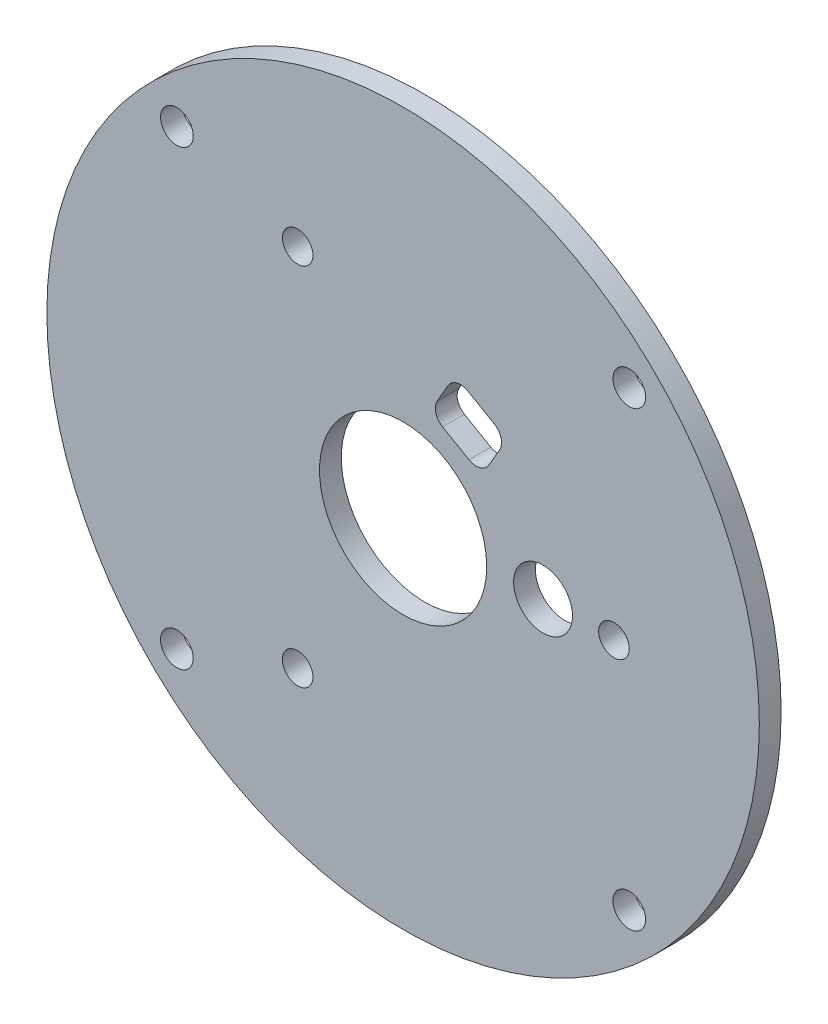
SolidWorks part; units mm, degrees
ref_plane "前视基准面" through (0, 0, 0) normal (0, 0, 1) x (1, 0, 0)
ref_plane "上视基准面" through (0, 0, 0) normal (0, 1, 0) x (1, 0, 0)
ref_plane "右视基准面" through (0, 0, 0) normal (1, 0, 0) x (0, 0, -1)
sketch "草图1" plane through (0, 0, 0) normal (0, 0, 1) x (1, 0, 0)
  line L10 (0, 0) -> (29, 0)
  line L11 (0, 0) -> (-14.5, 25.1147)
  line L12 (0, 0) -> (-14.5, -25.1147)
  circle A2 centre (0, 44) radius 1.6
  circle A4 centre (0, 0) radius 49
  circle A5 centre (44, 0) radius 1.6
  circle A7 centre (0, -44) radius 1.6
  circle A9 centre (-44, 0) radius 1.6
  circle A10 centre (29, 0) radius 2.1
  circle A11 centre (-14.5, 25.1147) radius 2.1
  circle A12 centre (-14.5, -25.1147) radius 2.1
  point P34 (0, 0)
  dimension "D1" = 4
sketch "草图2" plane through (0, 0, 0) normal (0, 0, 1) x (1, 0, 0)
  circle A0 centre (0, 0) radius 11.5
sketch "草图3" plane through (0, 0, 0) normal (0, 0, 1) x (1, 0, 0)
  circle A0 centre (0, 0) radius 8.6
sketch "草图5" plane through (0, 0, 0) normal (1, 0, 0) x (0, 0, -1)
  circle A0 centre (-59.5, 0) radius 1.5
sketch "草图6" plane through (0, 0, 0) normal (0, 0, 1) x (1, 0, 0)
  circle A0 centre (19.25, 0) radius 4.05
sketch "草图7" plane through (0, 0, 0) normal (0, 0, 1) x (1, 0, 0)
  line L3 (10.8022, 10.5058) -> (14.2725, 16.5146)
  line L8 (3.7014, 14.6068) -> (10.8022, 10.5058)
  line L9 (3.7014, 14.6068) -> (7.1717, 20.6156)
  line L10 (7.1717, 20.6156) -> (14.2725, 16.5146)
  dimension "D1" = 14.5
extrude "凸台-拉伸4" add sketch "草图1" along normal blind 13 contours A2 | A7 | A5 | A9 | A12 | A10 | A11
sketch "草图8" plane through (0, 0, 0) normal (0, 0, 1) x (1, 0, 0)
  circle A0 centre (0, 0) radius 49
extrude "凸台-拉伸5" add sketch "草图8" along normal blind 3
sketch "草图9" plane through (0, 0, 0) normal (0, 0, 1) x (1, 0, 0)
  circle A0 centre (0, 44) radius 2.1
  circle A1 centre (44, 0) radius 2.1
  circle A2 centre (0, -44) radius 2.1
  circle A3 centre (-44, 0) radius 2.1
  circle A4 centre (-14.5, 25.1147) radius 2.1
  circle A5 centre (-14.5, -25.1147) radius 2.1
  circle A6 centre (29, 0) radius 2.1
  point P12 (0, 0)
  dimension "D2" = 4.2
  dimension "D1" = 4
extrude "切除-拉伸2" cut sketch "草图9" along normal blind 13
extrude "切除-拉伸3" cut sketch "草图3" along normal blind 13 contours A0
extrude "切除-拉伸4" cut sketch "草图6" along normal blind 13 contours A0
extrude "切除-拉伸5" cut sketch "草图7" along normal blind 13 contours L10 L3 L8 L9
extrude "切除-拉伸6" cut sketch "草图2" along normal blind 13 contours A0
fillet "圆角1" radius 2 4 edges at (7.1717, 20.6156, 1.5) (14.2725, 16.5146, 1.5) (10.8022, 10.5058, 1.5) (3.7014, 14.6068, 1.5)
sketch "草图10" plane through (0, 0, 3) normal (0, 0, 1) x (1, 0, 0)
  line L0 (-31.1127, 31.1127) -> (31.1127, -31.1127) construction
  line L1 (-31.1127, -31.1127) -> (31.1127, 31.1127) construction
  line L2 (-44, 0) -> (44, 0) construction
  circle A0 centre (0, 0) radius 44 construction
  circle A1 centre (-31.1127, 31.1127) radius 2.25
  circle A2 centre (31.1127, 31.1127) radius 2.25
  circle A3 centre (31.1127, -31.1127) radius 2.25
  circle A4 centre (-31.1127, -31.1127) radius 2.25
  dimension "D3" = 4.5
  dimension "D1" = 45
  dimension "D2" = 45
extrude "切除-拉伸7" cut sketch "草图10" against normal up to next
sketch "草图11" plane through (0, 0, 3) normal (0, 0, 1) x (1, 0, 0)
  circle A0 centre (-44, 0) radius 2.1
  circle A1 centre (0, -44) radius 2.1
  circle A2 centre (44, 0) radius 2.1
  circle A3 centre (0, 44) radius 2.1
extrude "凸台-拉伸6" add sketch "草图11" against normal up to surface (3 mm away) up to face at (-28.8627, -31.1127, 0)
